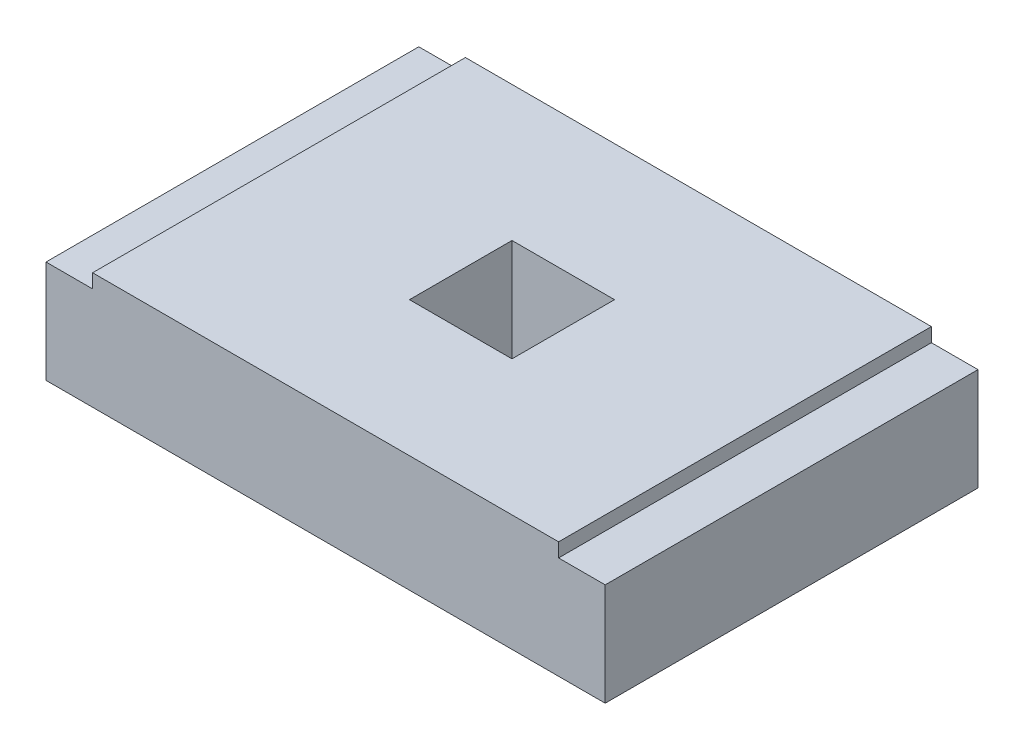
SolidWorks part; units mm, degrees
ref_plane "Front Plane" through (0, 0, 0) normal (0, 0, 1) x (1, 0, 0)
ref_plane "Top Plane" through (0, 0, 0) normal (0, 1, 0) x (1, 0, 0)
ref_plane "Right Plane" through (0, 0, 0) normal (1, 0, 0) x (0, 0, -1)
sketch "Sketch1" plane through (0, 0, 0) normal (0, 0, 1) x (1, 0, 0)
  line L0 (-50, 12.5) -> (-50, 9.5)
  line L1 (60, 12.5) -> (-60, 12.5)
  line L2 (60, 12.5) -> (60, -12.5)
  line L3 (60, -12.5) -> (-60, -12.5)
  line L4 (-60, 12.5) -> (-60, -12.5)
  line L5 (60, 12.5) -> (-60, -12.5) construction
  line L6 (60, -12.5) -> (-60, 12.5) construction
  line L7 (-50, 9.5) -> (50, 9.5)
  line L8 (50, 9.5) -> (50, 12.5)
  line L9 (-50, 9.5) -> (-60, 9.5)
  line L10 (50, 9.5) -> (60, 9.5)
  point P0 (0, 0)
  point P8 (0, 9.5)
  dimension "D1" = 120
  dimension "D2" = 25
  dimension "D3" = 3
  dimension "D4" = 100
extrude "Boss-Extrude1" add sketch "Sketch1" along normal mid plane 80 contours L10 L7 L9 L4 L3 L2 | L7 L8 L1 L0
sketch "Sketch2" plane through (0, 12.5, 0) normal (0, 1, 0) x (1, 0, 0)
  line L1 (-11, -11) -> (11, -11)
  line L2 (-11, -11) -> (-11, 11)
  line L3 (-11, 11) -> (11, 11)
  line L4 (11, -11) -> (11, 11)
  line L5 (-11, -11) -> (11, 11) construction
  line L6 (-11, 11) -> (11, -11) construction
  point P0 (0, 0)
  dimension "D1" = 22
extrude "Cut-Extrude1" cut sketch "Sketch2" against normal through all
